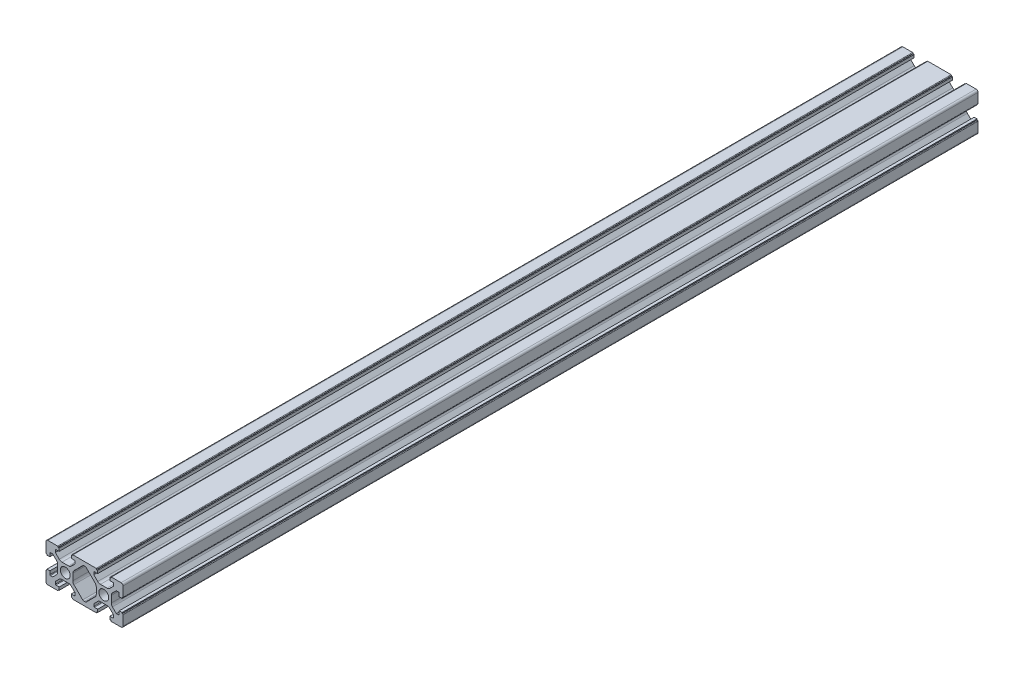
SolidWorks part; units mm, degrees
material "6063-T5"
ref_plane "Alzado" through (0, 0, 0) normal (0, 0, 1) x (1, 0, 0)
ref_plane "Planta" through (0, 0, 0) normal (0, 1, 0) x (1, 0, 0)
ref_plane "Vista lateral" through (0, 0, 0) normal (1, 0, 0) x (0, 0, -1)
sketch "Croquis1" plane through (0, 0, 0) normal (0, 0, 1) x (1, 0, 0)
  line L0 (-20, -9) -> (-20, -3.95)
  line L1 (-19.7, -3.65) -> (-19.5, -3.65)
  line L2 (-19.5, -3.65) -> (-19.5, -3.15)
  line L3 (-19.5, -3.15) -> (-18, -3.15)
  line L4 (-18, -3.15) -> (-18, -4.85)
  line L5 (-13.9, -1.7216) -> (-13.9, 1.7216)
  line L6 (-18, 3.15) -> (-18, 4.85)
  line L7 (-19.5, 3.15) -> (-18, 3.15)
  line L8 (-19.5, 3.65) -> (-19.5, 3.15)
  line L9 (-19.7, 3.65) -> (-19.5, 3.65)
  line L10 (-20, 9) -> (-20, 3.95)
  line L11 (-17.7, 5.15) -> (-16.5, 5.15)
  line L12 (-16.5, 5.15) -> (-14.4858, 3.1358)
  line L13 (-16.5, -5.15) -> (-14.4858, -3.1358)
  line L14 (-17.7, -5.15) -> (-16.5, -5.15)
  line L15 (-4.85, 7.7) -> (-4.85, 6.5)
  line L16 (-4.85, 6.5) -> (-6.8642, 4.4858)
  line L17 (-15.15, 6.5) -> (-13.1358, 4.4858)
  line L18 (-15.15, 7.7) -> (-15.15, 6.5)
  line L19 (-19, 10) -> (-13.95, 10)
  line L20 (-13.65, 9.7) -> (-13.65, 9.5)
  line L21 (-13.65, 9.5) -> (-13.15, 9.5)
  line L22 (-13.15, 9.5) -> (-13.15, 8)
  line L23 (-13.15, 8) -> (-14.85, 8)
  line L24 (-8.2784, 3.9) -> (-11.7216, 3.9)
  line L25 (-6.85, 8) -> (-5.15, 8)
  line L26 (-6.85, 9.5) -> (-6.85, 8)
  line L27 (-6.35, 9.5) -> (-6.85, 9.5)
  line L28 (-6.35, 9.7) -> (-6.35, 9.5)
  line L29 (-6.1, 1.7216) -> (-6.1, -1.7216)
  line L30 (-3.5, 5.15) -> (-5.5142, 3.1358)
  line L31 (-15.15, -7.7) -> (-15.15, -6.5)
  line L32 (-15.15, -6.5) -> (-13.1358, -4.4858)
  line L33 (-4.85, -6.5) -> (-6.8642, -4.4858)
  line L34 (-4.85, -7.7) -> (-4.85, -6.5)
  line L35 (0, -10) -> (-6.05, -10)
  line L36 (-6.35, -9.7) -> (-6.35, -9.5)
  line L37 (-6.35, -9.5) -> (-6.85, -9.5)
  line L38 (-6.85, -9.5) -> (-6.85, -8)
  line L39 (-6.85, -8) -> (-5.15, -8)
  line L40 (-11.7216, -3.9) -> (-8.2784, -3.9)
  line L41 (-13.15, -8) -> (-14.85, -8)
  line L42 (-13.15, -9.5) -> (-13.15, -8)
  line L43 (-13.65, -9.5) -> (-13.15, -9.5)
  line L44 (-13.65, -9.7) -> (-13.65, -9.5)
  line L45 (-19, -10) -> (-13.95, -10)
  line L46 (6.1, -1.7216) -> (6.1, 1.7216)
  line L47 (3.5, 5.15) -> (5.5142, 3.1358)
  line L48 (15.15, 7.7) -> (15.15, 6.5)
  line L49 (15.15, 6.5) -> (13.1358, 4.4858)
  line L50 (4.85, 6.5) -> (6.8642, 4.4858)
  line L51 (4.85, 7.7) -> (4.85, 6.5)
  line L52 (6.35, 9.7) -> (6.35, 9.5)
  line L53 (6.35, 9.5) -> (6.85, 9.5)
  line L54 (6.85, 9.5) -> (6.85, 8)
  line L55 (6.85, 8) -> (5.15, 8)
  line L56 (11.7216, 3.9) -> (8.2784, 3.9)
  line L57 (13.15, 8) -> (14.85, 8)
  line L58 (13.15, 9.5) -> (13.15, 8)
  line L59 (13.65, 9.5) -> (13.15, 9.5)
  line L60 (13.65, 9.7) -> (13.65, 9.5)
  line L61 (19, 10) -> (13.95, 10)
  line L62 (20, 9) -> (20, 3.95)
  line L63 (19.7, 3.65) -> (19.5, 3.65)
  line L64 (19.5, 3.65) -> (19.5, 3.15)
  line L65 (19.5, 3.15) -> (18, 3.15)
  line L66 (18, 3.15) -> (18, 4.85)
  line L67 (13.9, 1.7216) -> (13.9, -1.7216)
  line L68 (18, -3.15) -> (18, -4.85)
  line L69 (19.5, -3.15) -> (18, -3.15)
  line L70 (19.5, -3.65) -> (19.5, -3.15)
  line L71 (19.7, -3.65) -> (19.5, -3.65)
  line L72 (20, -9) -> (20, -3.95)
  line L73 (17.7, -5.15) -> (16.5, -5.15)
  line L74 (16.5, -5.15) -> (14.4858, -3.1358)
  line L75 (16.5, 5.15) -> (14.4858, 3.1358)
  line L76 (17.7, 5.15) -> (16.5, 5.15)
  line L77 (4.85, -7.7) -> (4.85, -6.5)
  line L78 (4.85, -6.5) -> (6.8642, -4.4858)
  line L79 (15.15, -6.5) -> (13.1358, -4.4858)
  line L80 (15.15, -7.7) -> (15.15, -6.5)
  line L81 (19, -10) -> (13.65, -10)
  line L82 (13.65, -10) -> (13.65, -9.5)
  line L83 (13.65, -9.5) -> (13.15, -9.5)
  line L84 (13.15, -9.5) -> (13.15, -8)
  line L85 (13.15, -8) -> (14.85, -8)
  line L86 (8.2784, -3.9) -> (11.7216, -3.9)
  line L87 (6.85, -8) -> (5.15, -8)
  line L88 (6.85, -9.5) -> (6.85, -8)
  line L89 (6.35, -9.5) -> (6.85, -9.5)
  line L90 (6.35, -9.7) -> (6.35, -9.5)
  line L91 (0, -10) -> (6.05, -10)
  line L92 (-3.5, 5.15) -> (-0.9429, 7.7071)
  line L93 (3.5, 5.15) -> (0.9429, 7.7071)
  line L94 (-0.2358, 8) -> (0.2358, 8)
  line L95 (-6.05, 10) -> (6.05, 10)
  line L96 (-0.2358, -8) -> (0.2358, -8)
  line L97 (3.5, -5.15) -> (0.9429, -7.7071)
  line L98 (-3.5, -5.15) -> (-0.9429, -7.7071)
  line L99 (-3.5, -5.15) -> (-5.5142, -3.1358)
  line L100 (3.5, -5.15) -> (5.5142, -3.1358)
  arc A0 (-5.15, -8) -> (-4.85, -7.7) centre (-5.15, -7.7) ccw
  arc A1 (-15.15, -7.7) -> (-14.85, -8) centre (-14.85, -7.7) ccw
  arc A2 (-18, -4.85) -> (-17.7, -5.15) centre (-17.7, -4.85) ccw
  arc A3 (-17.7, 5.15) -> (-18, 4.85) centre (-17.7, 4.85) ccw
  arc A4 (-14.85, 8) -> (-15.15, 7.7) centre (-14.85, 7.7) ccw
  arc A5 (-4.85, 7.7) -> (-5.15, 8) centre (-5.15, 7.7) ccw
  arc A6 (-19.7, -3.65) -> (-20, -3.95) centre (-19.7, -3.95) ccw
  arc A7 (-20, 3.95) -> (-19.7, 3.65) centre (-19.7, 3.95) ccw
  arc A8 (-20, -9) -> (-19, -10) centre (-19, -9) ccw
  arc A9 (-19, 10) -> (-20, 9) centre (-19, 9) ccw
  circle A10 centre (-10, 0) radius 2.55
  arc A11 (-13.9, 1.7216) -> (-14.4858, 3.1358) centre (-15.9, 1.7216) ccw
  arc A12 (-14.4858, -3.1358) -> (-13.9, -1.7216) centre (-15.9, -1.7216) ccw
  arc A13 (-8.2784, 3.9) -> (-6.8642, 4.4858) centre (-8.2784, 5.9) ccw
  arc A14 (-13.1358, 4.4858) -> (-11.7216, 3.9) centre (-11.7216, 5.9) ccw
  arc A15 (-6.1, -1.7216) -> (-5.5142, -3.1358) centre (-4.1, -1.7216) ccw
  arc A16 (-5.5142, 3.1358) -> (-6.1, 1.7216) centre (-4.1, 1.7216) ccw
  arc A17 (-11.7216, -3.9) -> (-13.1358, -4.4858) centre (-11.7216, -5.9) ccw
  arc A18 (-6.8642, -4.4858) -> (-8.2784, -3.9) centre (-8.2784, -5.9) ccw
  arc A19 (17.7, -5.15) -> (18, -4.85) centre (17.7, -4.85) ccw
  arc A20 (14.85, -8) -> (15.15, -7.7) centre (14.85, -7.7) ccw
  arc A21 (4.85, -7.7) -> (5.15, -8) centre (5.15, -7.7) ccw
  arc A22 (5.15, 8) -> (4.85, 7.7) centre (5.15, 7.7) ccw
  arc A23 (15.15, 7.7) -> (14.85, 8) centre (14.85, 7.7) ccw
  arc A24 (18, 4.85) -> (17.7, 5.15) centre (17.7, 4.85) ccw
  arc A25 (20, -3.95) -> (19.7, -3.65) centre (19.7, -3.95) ccw
  arc A26 (19.7, 3.65) -> (20, 3.95) centre (19.7, 3.95) ccw
  arc A27 (19, -10) -> (20, -9) centre (19, -9) ccw
  arc A28 (20, 9) -> (19, 10) centre (19, 9) ccw
  circle A29 centre (10, 0) radius 2.55
  arc A30 (6.1, 1.7216) -> (5.5142, 3.1358) centre (4.1, 1.7216) ccw
  arc A31 (5.5142, -3.1358) -> (6.1, -1.7216) centre (4.1, -1.7216) ccw
  arc A32 (11.7216, 3.9) -> (13.1358, 4.4858) centre (11.7216, 5.9) ccw
  arc A33 (6.8642, 4.4858) -> (8.2784, 3.9) centre (8.2784, 5.9) ccw
  arc A34 (13.9, -1.7216) -> (14.4858, -3.1358) centre (15.9, -1.7216) ccw
  arc A35 (14.4858, 3.1358) -> (13.9, 1.7216) centre (15.9, 1.7216) ccw
  arc A36 (8.2784, -3.9) -> (6.8642, -4.4858) centre (8.2784, -5.9) ccw
  arc A37 (13.1358, -4.4858) -> (11.7216, -3.9) centre (11.7216, -5.9) ccw
  arc A38 (-0.2358, 8) -> (-0.9429, 7.7071) centre (-0.2358, 7) ccw
  arc A39 (0.9429, 7.7071) -> (0.2358, 8) centre (0.2358, 7) ccw
  arc A40 (0.2358, -8) -> (0.9429, -7.7071) centre (0.2358, -7) ccw
  arc A41 (-0.9429, -7.7071) -> (-0.2358, -8) centre (-0.2358, -7) ccw
  arc A42 (6.05, -10) -> (6.35, -9.7) centre (6.05, -9.7) ccw
  arc A43 (-6.35, -9.7) -> (-6.05, -10) centre (-6.05, -9.7) ccw
  arc A44 (-13.95, -10) -> (-13.65, -9.7) centre (-13.95, -9.7) ccw
  arc A45 (13.95, 10) -> (13.65, 9.7) centre (13.95, 9.7) ccw
  arc A46 (6.35, 9.7) -> (6.05, 10) centre (6.05, 9.7) ccw
  arc A47 (-6.05, 10) -> (-6.35, 9.7) centre (-6.05, 9.7) ccw
  arc A48 (-13.65, 9.7) -> (-13.95, 10) centre (-13.95, 9.7) ccw
  point P199 (-20, 6.475)
  dimension "D1" = 20
  dimension "D2" = 40
extrude "Saliente-Extruir1" add sketch "Croquis1" along normal blind 444 contours A10 | L98 A41 L96 A40 L97 L100 A31 L46 A30 L47 L93 A39 L94 A38 L92 L30 A16 L29 A15 L99 | A29 | L19 A48 L20 L21 L22 L23 A4 L18 L17 A14 L24 A13 L16 L15 A5 L25 L26 L27 L28 A47 L95 A46 L52 L53 L54 L55 A22 L51 L50 A33 L56 A32 L49 L48 A23 L57 L58 L59 L60 A45 L61 A28 L62 A26 L63 L64 L65 L66 A24 L76 L75 A35 L67 A34 L74 L73 A19 L68 L69 L70 L71 A25 L72 A27 L81 L82 L83 L84 L85 A20 L80 L79 A37 L86 A36 L78 L77 A21 L87 L88 L89 L90 A42 L91 L35 A43 L36 L37 L38 L39 A0 L34 L33 A18 L40 A17 L32 L31 A1 L41 L42 L43 L44 A44 L45 A8 L0 A6 L1 L2 L3 L4 A2 L14 L13 A12 L5 A11 L12 L11 A3 L6 L7 L8 L9 A7 L10 A9
